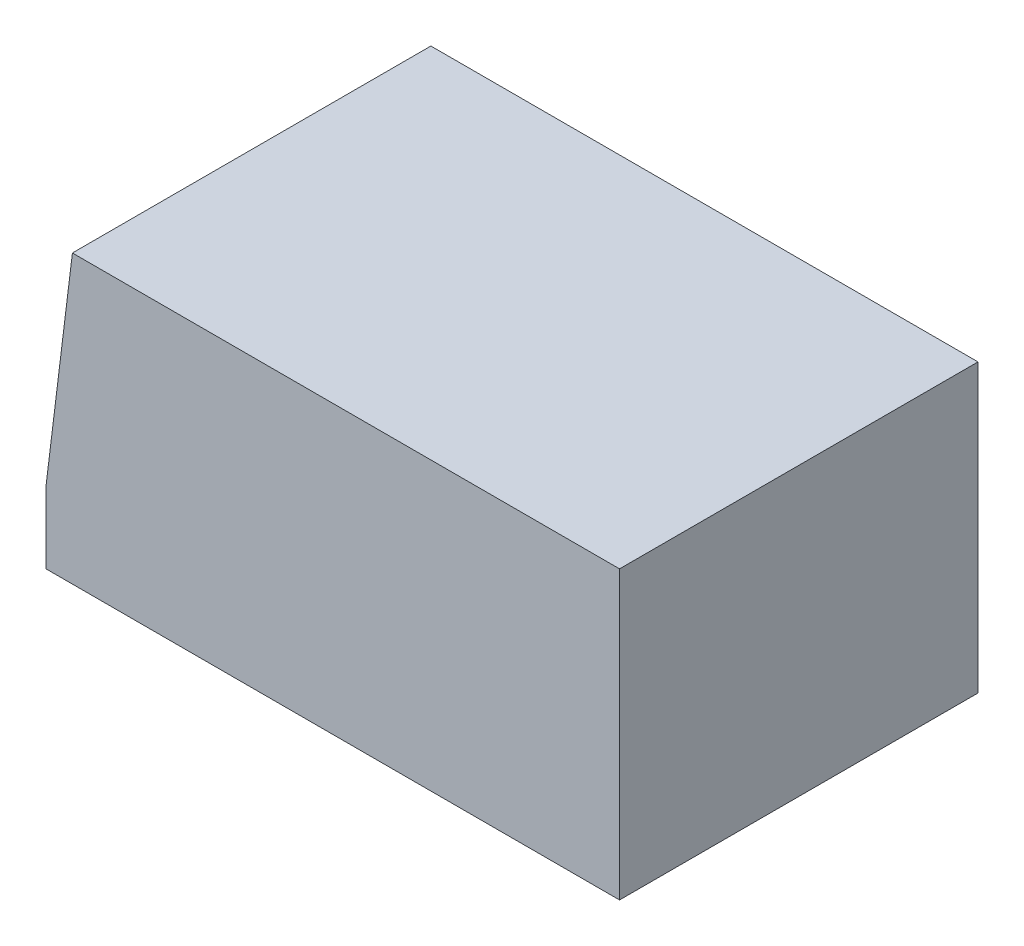
SolidWorks part; units mm, degrees
ref_plane "Plan de face" through (0, 0, 0) normal (0, 0, 1) x (1, 0, 0)
ref_plane "Plan de dessus" through (0, 0, 0) normal (0, 1, 0) x (1, 0, 0)
ref_plane "Plan de droite" through (0, 0, 0) normal (1, 0, 0) x (0, 0, -1)
sketch "Esquisse1" plane through (0, 0, 0) normal (0, 1, 0) x (1, 0, 0)
  line L1 (-40, -25) -> (40, -25)
  line L2 (-40, -25) -> (-40, 25)
  line L3 (-40, 25) -> (40, 25)
  line L4 (40, -25) -> (40, 25)
  line L5 (-40, -25) -> (40, 25) construction
  line L6 (-40, 25) -> (40, -25) construction
  point P0 (0, 0)
  dimension "D1" = 50
  dimension "D2" = 80
extrude "Boss.-Extru.1" add sketch "Esquisse1" along normal blind 40
chamfer "Chanfrein1" distance 30 angle 7 1 edges at (-40, 40, 0)
sketch "Esquisse2" plane through (-40.6155, 4.987, 0) normal (-0.9925, 0.1219, 0) x (0, 0, 1)
  line L0 (25, 18.821) -> (-25, 18.821) construction
  line L3 (25, 35.276) -> (25, 5.0507) construction
  line L4 (-25, 5.0507) -> (-25, 35.276) construction
  circle A0 centre (0, 18.821) radius 12.5
  dimension "D1" = 25
extrude "Enlèv. mat.-Extru.1" cut sketch "Esquisse2" against normal blind 40
